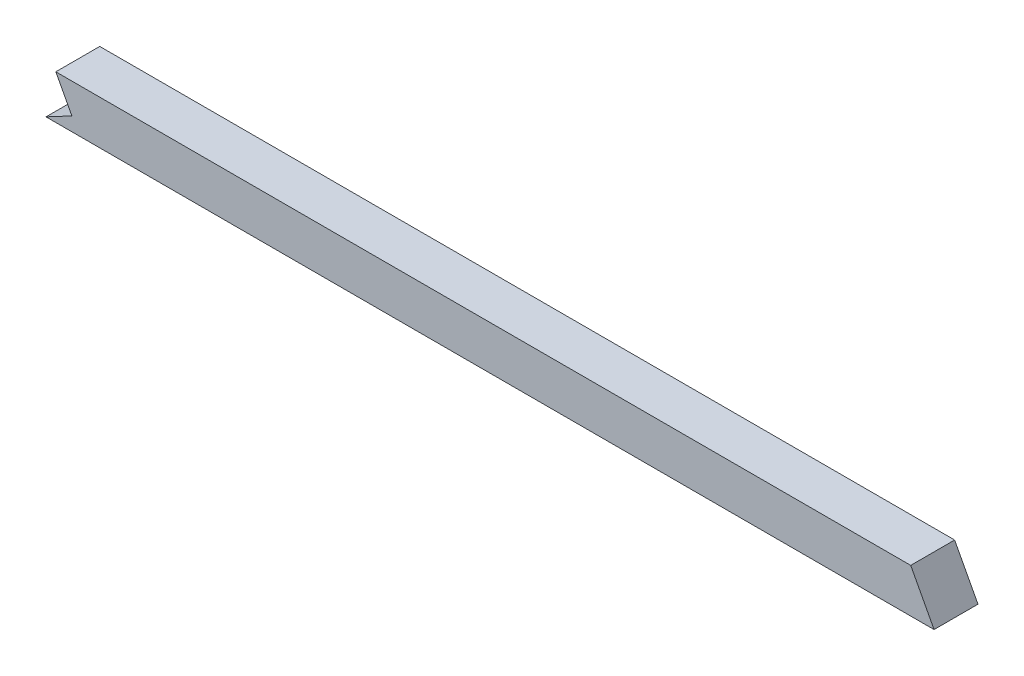
SolidWorks part; units mm, degrees
material "Pine"
ref_plane "X-Y Datum" through (0, 0, 0) normal (0, 0, 1) x (1, 0, 0)
ref_plane "X-Z Datum" through (0, 0, 0) normal (0, 1, 0) x (1, 0, 0)
ref_plane "Y-Z Datum" through (0, 0, 0) normal (1, 0, 0) x (0, 0, -1)
sketch "Sketch1" plane through (0, 0, 0) normal (1, 0, 0) x (0, 0, -1)
  line L1 (-19.05, 19.05) -> (19.05, 19.05)
  line L2 (-19.05, 19.05) -> (-19.05, -19.05)
  line L3 (-19.05, -19.05) -> (19.05, -19.05)
  line L4 (19.05, 19.05) -> (19.05, -19.05)
  line L5 (-19.05, 19.05) -> (19.05, -19.05) construction
  line L6 (-19.05, -19.05) -> (19.05, 19.05) construction
  point P0 (0, 0)
  dimension "D1" = 38.1
extrude "Boss-Extrude1" add sketch "Sketch1" along normal blind 770.128
sketch "Sketch2" plane through (0, 0, 19.05) normal (0, 0, 1) x (1, 0, 0)
  line L0 (770.128, -19.05) -> (749.8699, 19.05)
  line L1 (770.128, 19.05) -> (0, 19.05) construction
  line L5 (770.128, 19.05) -> (770.128, -19.05) construction
  line L6 (749.8699, 19.05) -> (770.128, 19.05)
  line L7 (770.128, 19.05) -> (770.128, -19.05)
  dimension "D1" = 28
extrude "Cut-Extrude1" cut sketch "Sketch2" against normal through all
sketch "Sketch3" plane through (0, 0, 19.05) normal (0, 0, 1) x (1, 0, 0)
  line L6 (0, -19.05) -> (22.4269, -7.1254)
  line L7 (22.4269, -7.1254) -> (-1.4223, 37.7283)
  line L8 (-1.4223, 37.7283) -> (-23.8492, 25.8037)
  line L9 (-23.8492, 25.8037) -> (0, -19.05)
  line L10 (770.128, -19.05) -> (0, -19.05) construction
  dimension "D1" = 28
  dimension "D2" = 25.4
  dimension "D3" = 50.8
extrude "Cut-Extrude2" cut sketch "Sketch3" against normal through all both
